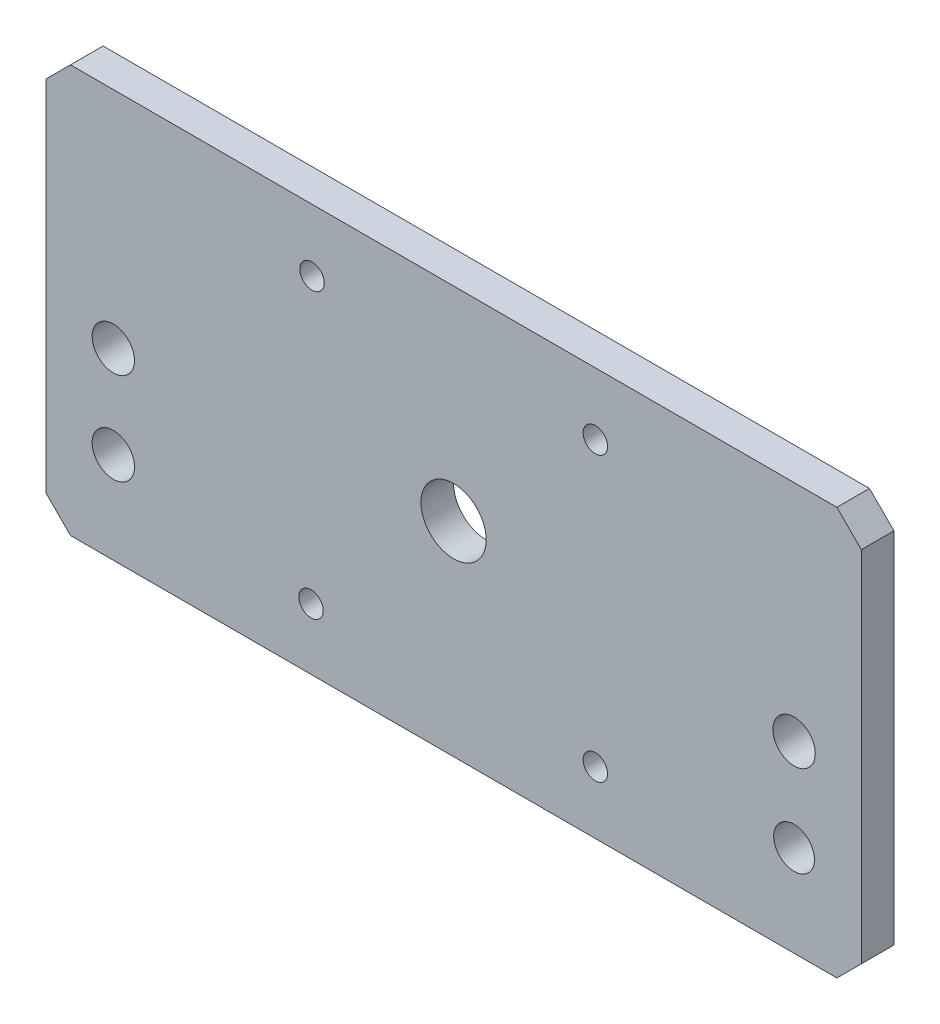
SolidWorks part; units mm, degrees
ref_plane "Front Plane" through (0, 0, 0) normal (0, 0, 1) x (1, 0, 0)
ref_plane "Top Plane" through (0, 0, 0) normal (0, 1, 0) x (1, 0, 0)
ref_plane "Right Plane" through (0, 0, 0) normal (1, 0, 0) x (0, 0, -1)
sketch "Esquisse1" plane through (0, 0, 0) normal (0, 0, 1) x (1, 0, 0)
  line L1 (-10, 0) -> (90, 0)
  line L2 (-10, 0) -> (-10, -50)
  line L3 (-10, -50) -> (90, -50)
  line L4 (90, 0) -> (90, -50)
  line L5 (-10, 0) -> (90, -50) construction
  line L6 (-10, -50) -> (90, 0) construction
  point P4 (40, -25)
  point P6 (0, 0)
  point P7 (-6.8583, 0)
  dimension "D1" = 50
  dimension "D2" = 100
  dimension "D3" = 10
extrude "Boss.-Extru.1" add sketch "Esquisse1" along normal blind 4
sketch "Esquisse2" plane through (0, 0, 0) normal (0, 0, -1) x (-1, 0, 0)
  circle A0 centre (-22.625, -7.625) radius 1.5
  circle A1 centre (-57.375, -42.375) radius 1.5
  circle A2 centre (-57.375, -7.625) radius 1.5
  circle A3 centre (-22.5, -42.5) radius 1.5
  dimension "D1" = 3
extrude "Enlèv. mat.-Extru.1" cut sketch "Esquisse2" against normal through all
sketch "Esquisse3" plane through (0, 0, 0) normal (0, 0, -1) x (-1, 0, 0)
  circle A0 centre (-39.9849, -24.9737) radius 4
  dimension "D1" = 8
extrude "Enlèv. mat.-Extru.2" cut sketch "Esquisse3" against normal through all
fillet "Congé1" radius 3 4 edges at (90, -50, 2) (-10, -50, 2) (-10, 0, 2) (90, 0, 2) profile chamfer
sketch "Esquisse4" plane through (0, 0, 4) normal (0, 0, 1) x (1, 0, 0)
  circle A0 centre (81.75, -27.5) radius 2.6
  circle A1 centre (81.75, -38.8) radius 2.4985
  circle A2 centre (-1.75, -27.5) radius 2.6
  circle A3 centre (-1.75, -38.8) radius 2.6
extrude "Enlèv. mat.-Extru.3" cut sketch "Esquisse4" against normal through all
